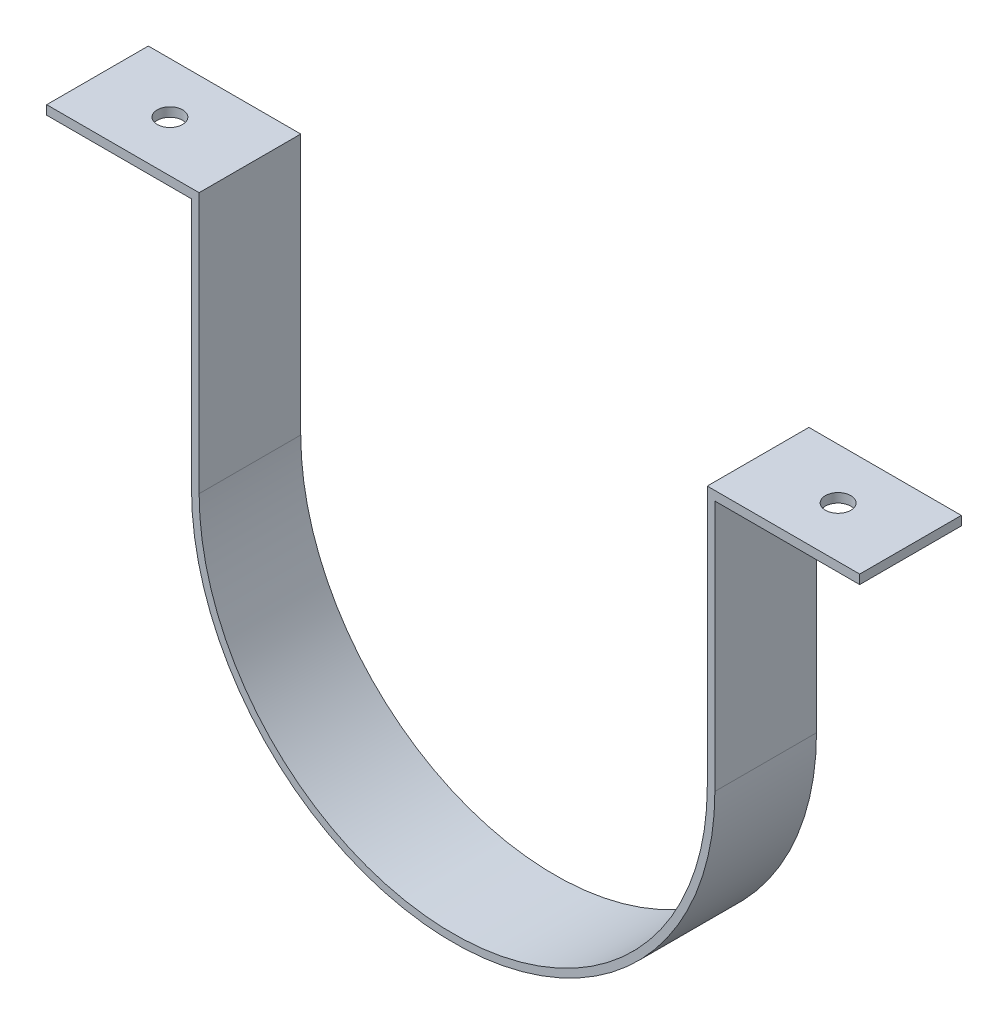
SolidWorks part; units mm, degrees
ref_plane "Plano frontal" through (0, 0, 0) normal (0, 0, 1) x (1, 0, 0)
ref_plane "Plano superior" through (0, 0, 0) normal (0, 1, 0) x (1, 0, 0)
ref_plane "Plano direito" through (0, 0, 0) normal (1, 0, 0) x (0, 0, -1)
sketch "Esboço1" plane through (0, 0, 0) normal (0, 0, 1) x (1, 0, 0)
  line L0 (101.6784, -2.5708) -> (101.6784, -7.7208)
  line L3 (101.8284, -7.7208) -> (101.8284, -2.7708)
  line L4 (96.6784, -2.5708) -> (101.6784, -2.5708) construction
  line L5 (101.6784, -2.5708) -> (91.6784, -2.5708) construction
  line L7 (91.6784, -2.5708) -> (101.6784, -2.5708) construction
  line L8 (96.6784, -2.7208) -> (96.6784, -2.5708) construction
  line L11 (91.5284, -7.7208) -> (91.5284, -2.7708)
  line L13 (91.6784, -2.5708) -> (91.6784, -7.804)
  line L15 (91.5284, -2.7708) -> (88.6784, -2.7708)
  line L16 (91.6784, -2.5708) -> (91.6784, -2.5908)
  line L17 (91.6784, -2.5908) -> (88.6784, -2.5908)
  line L18 (88.6784, -2.7708) -> (88.6784, -2.5908)
  line L19 (101.8284, -2.7708) -> (104.6784, -2.7708)
  line L20 (101.6784, -2.5708) -> (101.6784, -2.5908)
  line L21 (101.6784, -2.5908) -> (104.6784, -2.5908)
  line L22 (104.6784, -2.7708) -> (104.6784, -2.5908)
  arc A1 (91.6784, -7.7208) -> (101.6784, -7.7208) centre (96.6784, -7.7208) ccw
  arc A2 (91.5284, -7.7208) -> (101.8284, -7.7208) centre (96.6784, -7.7208) ccw
  circle A3 centre (96.6784, -7.7208) radius 5.15 construction
  circle A4 centre (96.6784, -7.7208) radius 5 construction
  dimension "D2" = 2.85
  dimension "D3" = 2.85
  dimension "D4" = 10
  dimension "D1" = 0.15
extrude "Ressalto-extrusão1" add sketch "Esboço1" along normal blind 2
sketch "Esboço2" plane through (0, -2.7708, 0) normal (0, -1, 0) x (1, 0, 0)
  line L0 (88.6784, 2) -> (91.5284, 0) construction
  line L1 (101.8284, 2) -> (104.6784, 0) construction
  line L4 (88.6784, 0) -> (91.5284, 0)
  line L5 (91.5284, 0) -> (91.5284, 2)
  line L6 (91.5284, 2) -> (88.6784, 2)
  line L7 (88.6784, 2) -> (88.6784, 0)
  line L8 (88.6784, 0) -> (91.5284, 0)
  line L9 (91.5284, 0) -> (91.5284, 2)
  line L10 (91.5284, 2) -> (88.6784, 2)
  line L11 (88.6784, 2) -> (88.6784, 0)
  line L12 (101.8284, 0) -> (104.6784, 0)
  line L13 (104.6784, 0) -> (104.6784, 2)
  line L14 (104.6784, 2) -> (101.8284, 2)
  line L15 (101.8284, 2) -> (101.8284, 0)
  line L16 (101.8284, 0) -> (104.6784, 0)
  line L17 (104.6784, 0) -> (104.6784, 2)
  line L18 (104.6784, 2) -> (101.8284, 2)
  line L19 (101.8284, 2) -> (101.8284, 0)
  circle A0 centre (90.1034, 1) radius 0.25
  circle A1 centre (103.2534, 1) radius 0.25
  point P12 (103.2534, 1)
  dimension "D1" = 0
  dimension "D2" = 0
extrude "Corte-extrusão2" cut sketch "Esboço2" against normal blind 2 contours A0 | A1
